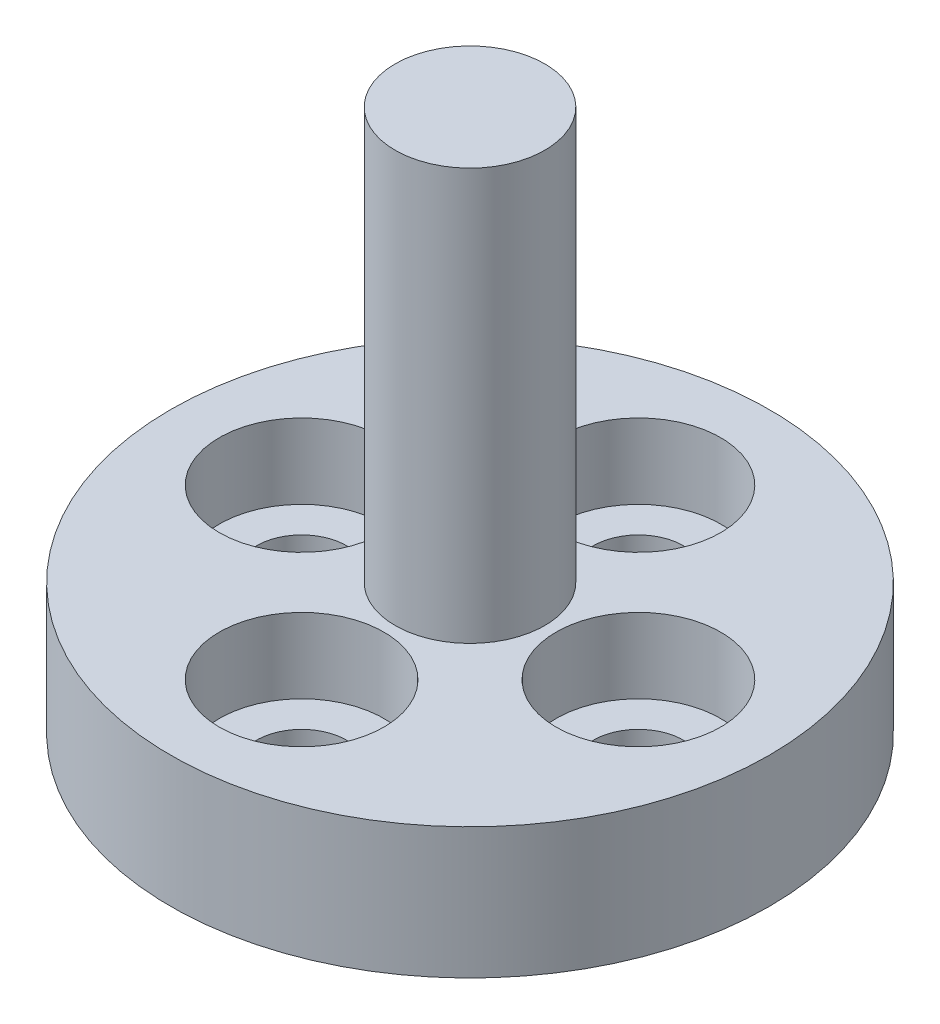
SolidWorks part; units mm, degrees
ref_plane "Front Plane" through (0, 0, 0) normal (0, 0, 1) x (1, 0, 0)
ref_plane "Top Plane" through (0, 0, 0) normal (0, 1, 0) x (1, 0, 0)
ref_plane "Right Plane" through (0, 0, 0) normal (1, 0, 0) x (0, 0, -1)
sketch "Sketch1" plane through (0, 0, 0) normal (0, 0, 1) x (1, 0, 0)
  line L0 (0, 14.5) -> (0, 0)
  line L1 (0, 0) -> (8, 0)
  line L2 (8, 0) -> (8, 3.5)
  line L3 (8, 3.5) -> (2, 3.5)
  line L4 (2, 14.5) -> (2, 3.5)
  line L5 (0, 14.5) -> (2, 14.5)
  dimension "D1" = 8
  dimension "D2" = 14.5
  dimension "D3" = 11
  dimension "D4" = 2
revolve "Revolve18" add sketch "Sketch1" angle 360 about L0
sketch "Sketch2" plane through (0, 3.5, 0) normal (0, 1, 0) x (1, 0, 0)
  circle A1 centre (0, 0) radius 4.5
  dimension "D1" = 9
hole_wizard "CBORE for M2 SHCS1" positions "Sketch3" profile "Sketch4" counterbore size "M2" standard "ANSI Metric" end condition through all
sketch "Sketch3" plane through (0, 3.5, 0) normal (0, 1, 0) x (1, 0, 0)
  circle A0 centre (0, 0) radius 4.5 construction
  point P0 (-4.5, 0)
  point P4 (0, 4.5)
  point P6 (4.5, 0)
  point P8 (0, -4.5)
sketch "Sketch4" plane through (-4.5, 3.5, 0) normal (1, 0, 0) x (0, 0, 1)
  line L0 (0, 0) -> (0, 3.5)
  line L1 (0, 3.5) -> (1.2, 3.5)
  line L3 (1.2, 3.5) -> (1.2, 2)
  line L4 (1.2, 2) -> (2.2, 2)
  line L5 (2.2, 2) -> (2.2, 0)
  line L7 (2.2, 0) -> (0, 0)
  line L11 (0, -6.35) -> (0, 107.95) construction
  dimension "Thru Hole Dia." = 2.4
  dimension "Thru Hole Depth" = 3.5
  dimension "C'Bore Dia." = 4.4
  dimension "C'Bore Depth" = 2
